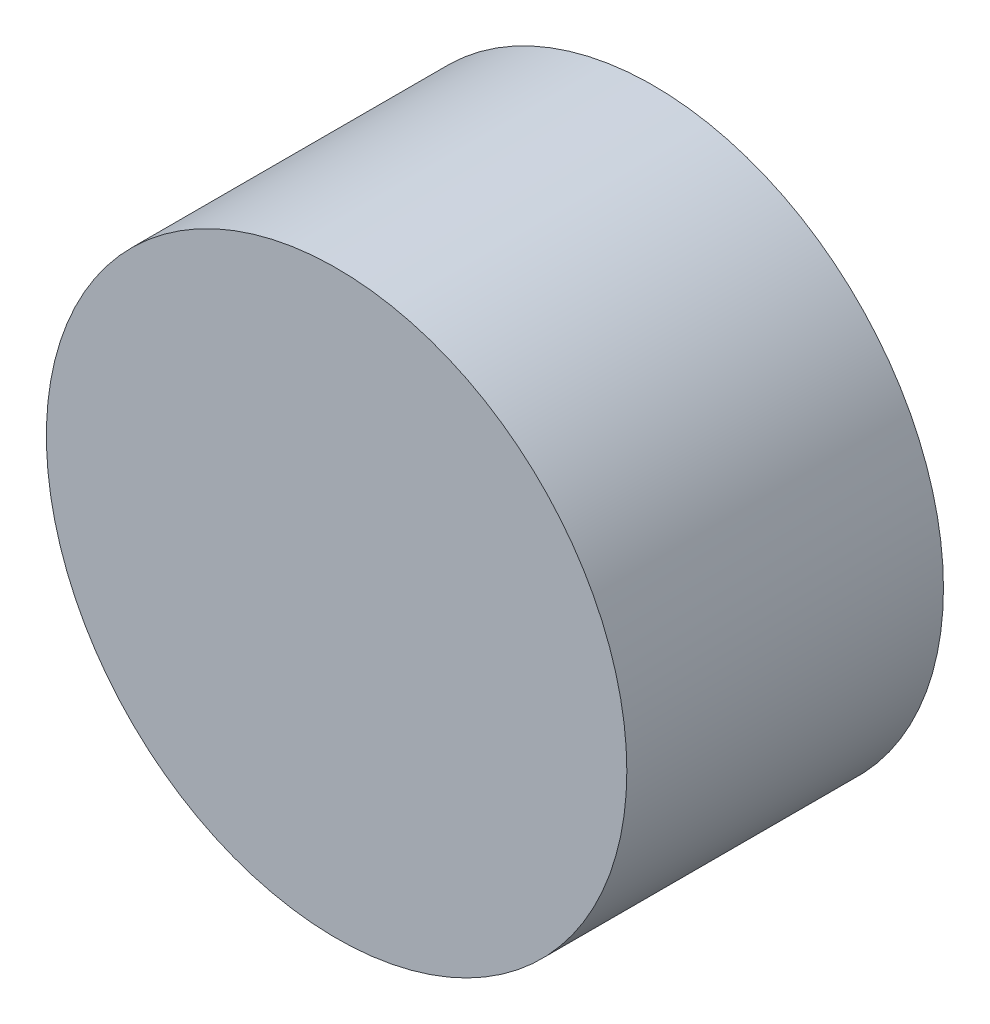
SolidWorks part; units mm, degrees
ref_plane "Front Plane" through (0, 0, 0) normal (0, 0, 1) x (1, 0, 0)
ref_plane "Top Plane" through (0, 0, 0) normal (0, 1, 0) x (1, 0, 0)
ref_plane "Right Plane" through (0, 0, 0) normal (1, 0, 0) x (0, 0, -1)
sketch "Sketch1" plane through (0, 0, 0) normal (0, 0, 1) x (1, 0, 0)
  circle A0 centre (0, 0) radius 2.75
  dimension "D1" = 5.5
extrude "Boss-Extrude1" add sketch "Sketch1" along normal blind 3
